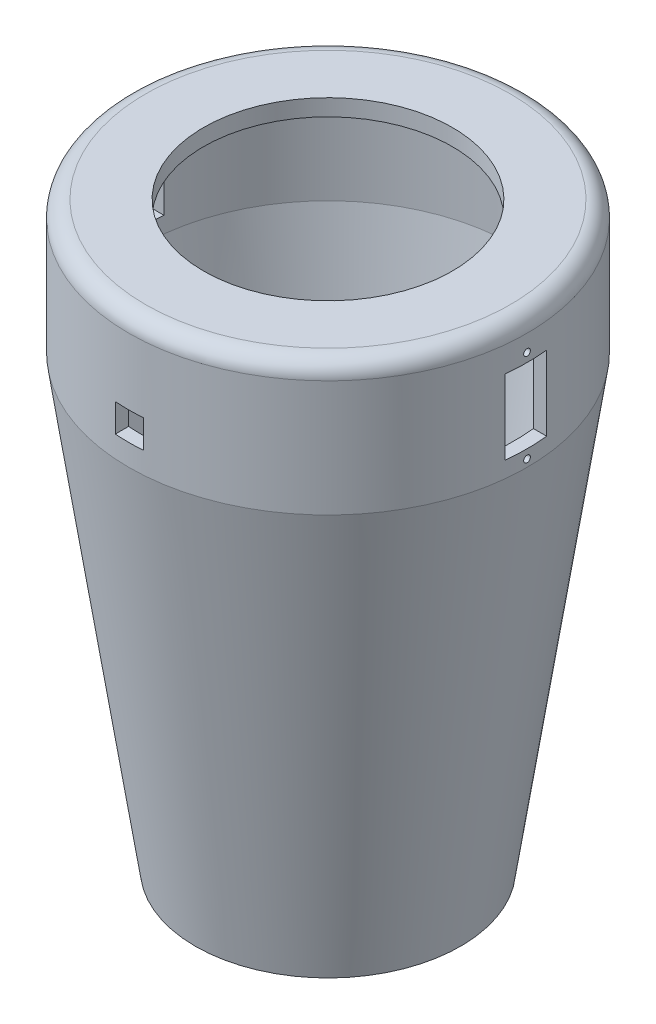
SolidWorks part; units mm, degrees
ref_plane "Front Plane" through (0, 0, 0) normal (0, 0, 1) x (1, 0, 0)
ref_plane "Top Plane" through (0, 0, 0) normal (0, 1, 0) x (1, 0, 0)
ref_plane "Right Plane" through (0, 0, 0) normal (1, 0, 0) x (0, 0, -1)
sketch "Sketch2" plane through (0, 0, 0) normal (0, 0, 1) x (1, 0, 0)
  line L0 (35, -5) -> (40, -5)
  line L1 (0, 170) -> (60, 170)
  line L2 (60, 170) -> (60, 130)
  line L3 (60, 130) -> (40, -5)
  line L5 (0, 165) -> (56, 165)
  line L6 (56, 165) -> (56, 130)
  line L7 (0, 170) -> (0, 165)
  line L8 (56, 130) -> (35, -5)
  line L9 (0, 170) -> (0, -37.0944) construction
  line L10 (0, -55) -> (0, 55) construction
  dimension "D2" = 60
  dimension "D3" = 175
  dimension "D4" = 40
  dimension "D5" = 5
  dimension "D6" = 56
  dimension "D7" = 35
revolve "Revolve1" add sketch "Sketch2" angle 360 about L9
ref_plane "Plane2" through (60, 0, 0) normal (1, 0, 0) x (0, 0, -1)
sketch "Sketch4" plane through (60, 0, 0) normal (1, 0, 0) x (0, 0, -1)
  line L0 (0, 66.0688) -> (0, -66.0688) construction
  line L1 (60, 170) -> (-60, 170) construction
  line L2 (0, 160) -> (0, 132.2) construction
  line L4 (-6.25, 157.35) -> (6.25, 157.35)
  line L5 (-6.25, 157.35) -> (-6.25, 134.85)
  line L6 (-6.25, 134.85) -> (6.25, 134.85)
  line L7 (6.25, 157.35) -> (6.25, 134.85)
  line L8 (-6.25, 157.35) -> (6.25, 134.85) construction
  line L9 (-6.25, 134.85) -> (6.25, 157.35) construction
  circle A0 centre (0, 132.2) radius 1
  circle A1 centre (0, 160) radius 1
  point P8 (0, 146.1)
  dimension "D1" = 27.8
  dimension "D2" = 10
  dimension "D3" = 12.5
  dimension "D4" = 22.5
extrude "Cut-Extrude2" cut sketch "Sketch4" against normal through all
sketch "Sketch5" plane through (0, 170, 0) normal (0, 1, 0) x (1, 0, 0)
  circle A0 centre (0, 0) radius 37.5
  dimension "D1" = 75
extrude "Cut-Extrude3" cut sketch "Sketch5" against normal up to next
fillet "Fillet1" radius 5 1 edges at (0, 170, 60)
ref_plane "Plane3" through (0, 0, 60) normal (0, 0, 1) x (1, 0, 0)
sketch "Sketch6" plane through (0, 0, 60) normal (0, 0, 1) x (1, 0, 0)
  line L0 (0, -66) -> (0, 66) construction
  line L1 (-4.25, 145) -> (4.25, 145)
  line L2 (-4.25, 145) -> (-4.25, 136.5)
  line L3 (-4.25, 136.5) -> (4.25, 136.5)
  line L4 (4.25, 145) -> (4.25, 136.5)
  line L5 (-4.25, 145) -> (4.25, 136.5) construction
  line L6 (-4.25, 136.5) -> (4.25, 145) construction
  line L7 (60, 165) -> (-60, 165) construction
  point P0 (0, 140.75)
  dimension "D1" = 8.5
  dimension "D2" = 8.5
  dimension "D3" = 20
extrude "Cut-Extrude4" cut sketch "Sketch6" against normal up to next contours L4 L3 L2 L1
